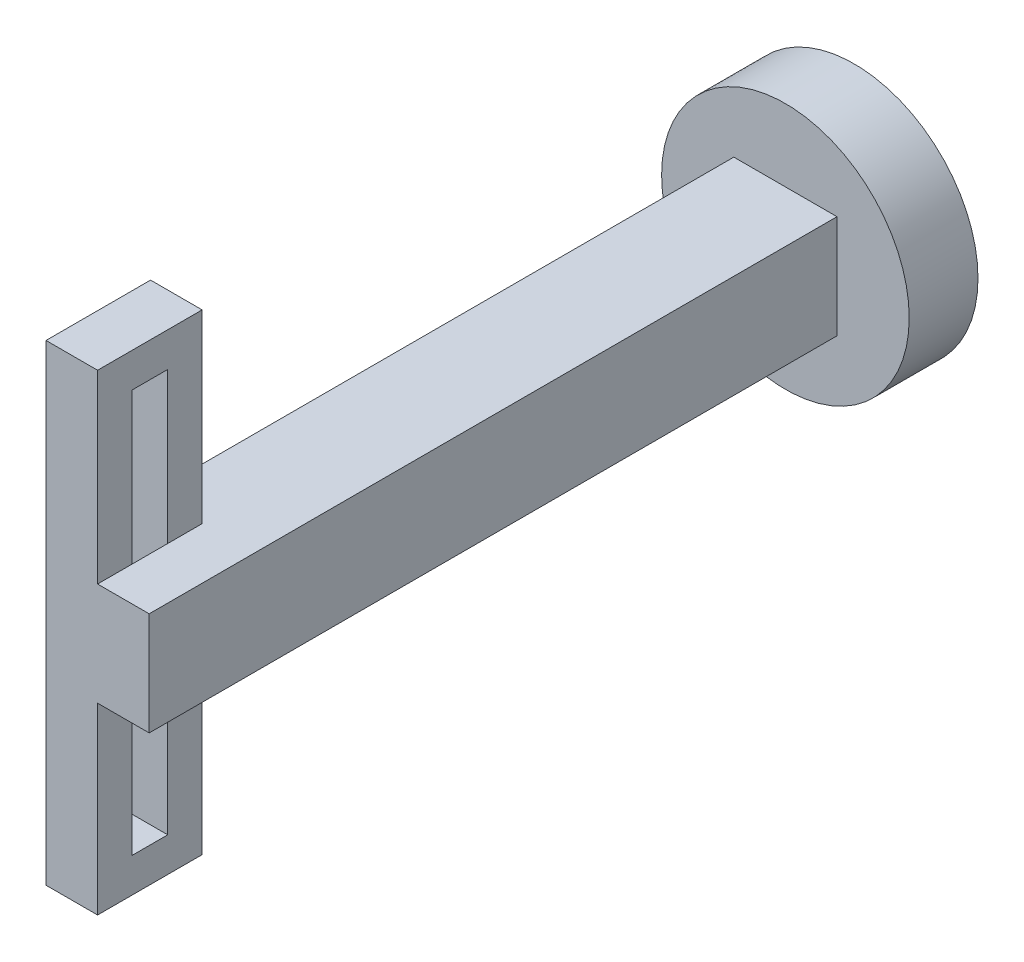
SolidWorks part; units mm, degrees
ref_plane "Front Plane" through (0, 0, 0) normal (0, 0, 1) x (1, 0, 0)
ref_plane "Top Plane" through (0, 0, 0) normal (0, 1, 0) x (1, 0, 0)
ref_plane "Right Plane" through (0, 0, 0) normal (1, 0, 0) x (0, 0, -1)
sketch "Sketch1" plane through (0, 0, 0) normal (0, 0, 1) x (1, 0, 0)
  circle A0 centre (0, 0) radius 3.6
  dimension "D1" = 7.2
extrude "Boss-Extrude1" add sketch "Sketch1" along normal blind 2
sketch "Sketch2" plane through (0, 0, 2) normal (0, 0, 1) x (1, 0, 0)
  line L1 (-1.5, -1.5) -> (1.5, -1.5)
  line L2 (-1.5, -1.5) -> (-1.5, 1.5)
  line L3 (-1.5, 1.5) -> (1.5, 1.5)
  line L4 (1.5, -1.5) -> (1.5, 1.5)
  line L5 (-1.5, -1.5) -> (1.5, 1.5) construction
  line L6 (-1.5, 1.5) -> (1.5, -1.5) construction
  point P0 (0, 0)
  dimension "D1" = 3
  dimension "D2" = 3
extrude "Boss-Extrude2" add sketch "Sketch2" along normal blind 20
sketch "Sketch3" plane through (0, 1.5, 0) normal (0, 1, 0) x (1, 0, 0)
  line L0 (0, 0) -> (0, -50000) construction
  line L1 (-1.5, -22) -> (0, -22)
  line L2 (-1.5, -22) -> (-1.5, -18.96)
  line L3 (-1.5, -18.96) -> (0, -18.96)
  line L4 (0, -22) -> (0, -18.96)
  line L5 (3.6, 0) -> (-3.6, 0) construction
  point P9 (0, 0)
extrude "Cut-Extrude1" cut sketch "Sketch3" against normal up to surface (3 mm away) up to face at (0, -1.5, 12)
sketch "Sketch4" plane through (0, 0, 0) normal (-1, 0, 0) x (0, 0, 1)
  line L0 (18.96, -1.5) -> (18.96, 1.5) construction
  line L1 (18.96, -6.8355) -> (22, -6.8355)
  line L2 (18.96, -6.8355) -> (18.96, 6.8836)
  line L3 (18.96, 6.8836) -> (22, 6.8836)
  line L4 (22, -6.8355) -> (22, 6.8836)
  line L5 (18.96, -6.8355) -> (22, 6.8836) construction
  line L6 (18.96, 6.8836) -> (22, -6.8355) construction
  line L7 (22, -1.5) -> (22, 1.5) construction
  line L9 (19.96, -5.8355) -> (21, -5.8355)
  line L10 (19.96, -5.8355) -> (19.96, 5.8836)
  line L11 (19.96, 5.8836) -> (21, 5.8836)
  line L12 (21, -5.8355) -> (21, 5.8836)
  line L13 (19.96, -5.8355) -> (21, 5.8836) construction
  line L14 (19.96, 5.8836) -> (21, -5.8355) construction
  point P0 (20.48, 0.024)
  point P9 (20.48, 0.024)
  dimension "D1" = 1
  dimension "D2" = 1
extrude "Boss-Extrude3" add sketch "Sketch4" along normal up to surface (1.5 mm away) up to face at (-1.5, 0, 10.48)
